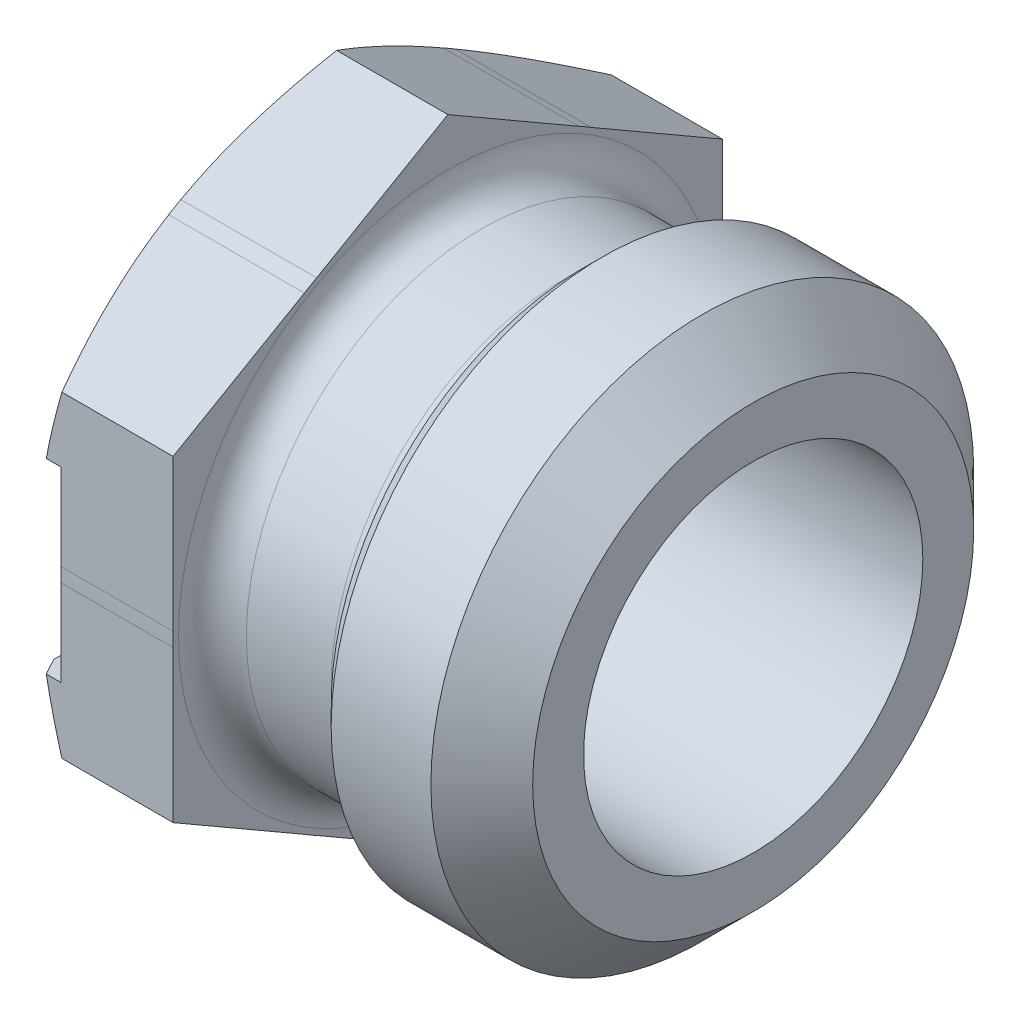
SolidWorks part; units mm, degrees
ref_plane "Спереди" through (0, 0, 0) normal (0, 0, 1) x (1, 0, 0)
ref_plane "Сверху" through (0, 0, 0) normal (0, 1, 0) x (1, 0, 0)
ref_plane "Справа" through (0, 0, 0) normal (1, 0, 0) x (0, 0, -1)
sketch "Эскиз1" plane through (0, 0, 0) normal (0, 1, 0) x (1, 0, 0)
  line L0 (24.8235, 0) -> (-21.6425, 0)
  line L1 (-8.6425, 0) -> (-8.6425, -6.5)
  line L2 (-8.6425, -6.5) -> (-10.1425, -8)
  line L3 (-10.1425, -8) -> (-13.6425, -8)
  line L4 (-13.6425, -8) -> (-13.6425, -7.44)
  line L5 (-14.1425, -6.94) -> (-16.6425, -6.94)
  line L6 (-17.6425, -7.94) -> (-17.6425, -9.35)
  line L7 (-17.6425, -9.35) -> (-20.9209, -9.35)
  line L8 (-20.9209, -9.35) -> (-21.6425, -8.1)
  line L9 (-21.6425, -8.1) -> (-21.6425, 0)
  line L10 (-8.6425, -5) -> (-21.6425, -5)
  line L11 (-13.6425, -7.44) -> (-13.0825, -8)
  arc A0 (-16.6425, -6.94) -> (-17.6425, -7.94) centre (-16.6425, -7.94) ccw
  arc A1 (-13.6425, -7.44) -> (-14.1425, -6.94) centre (-14.1425, -7.44) ccw
  point P18 (-17.6425, -6.94)
  point P21 (-13.6425, -6.94)
  dimension "D12" = 1
  dimension "D13" = 0.5
  dimension "D1" = 5
  dimension "D2" = 8
  dimension "D3" = 9
  dimension "D4" = 4
  dimension "D5" = 13
  dimension "D6" = 30
  dimension "D7" = 8.1
  dimension "D8" = 9.35
  dimension "D9" = 1.5
  dimension "D10" = 1.5
  dimension "D11" = 6.94
revolve "Повернуть1" add sketch "Эскиз1" angle 360 about L0
sketch "Эскиз2" plane through (-21.6425, 0, 0) normal (-1, 0, 0) x (0, 0, 1)
  line L1 (0, 9.35) -> (-8.0973, 4.675)
  line L2 (-8.0973, 4.675) -> (-8.0973, -4.675)
  line L3 (-8.0973, -4.675) -> (0, -9.35)
  line L4 (0, -9.35) -> (8.0973, -4.675)
  line L5 (8.0973, -4.675) -> (8.0973, 4.675)
  line L6 (8.0973, 4.675) -> (0, 9.35)
  circle A0 centre (0, 0) radius 8.0973 construction
  circle A1 centre (0, 0) radius 9.35
  circle M2 centre (0, 0) radius 8.1
extrude "Вырез-Вытянуть1" cut sketch "Эскиз2" against normal blind 10 contours L2 A1 M2 | L1 A1 M2 | L6 A1 M2 | L5 A1 M2 | L4 A1 M2 | L3 A1 M2
sketch "Эскиз3" plane through (0, 0, -8.0973) normal (0, 0, -1) x (-1, 0, 0)
  line L0 (21.6425, -0.2077) -> (21.6425, 0.2077) construction
  line L1 (22.3425, 2.75) -> (20.9425, 2.75)
  line L2 (22.3425, 2.75) -> (22.3425, -2.75)
  line L3 (22.3425, -2.75) -> (20.9425, -2.75)
  line L4 (20.9425, 2.75) -> (20.9425, -2.75)
  line L5 (22.3425, 2.75) -> (20.9425, -2.75) construction
  line L6 (22.3425, -2.75) -> (20.9425, 2.75) construction
  line L7 (21.6425, -6.9087) -> (21.6425, -0.2077) construction
  point P0 (21.6425, 0)
  dimension "D1" = 5.5
  dimension "D2" = 0.7
extrude "Вырез-Вытянуть2" cut sketch "Эскиз3" against normal through all both and the other way through all
